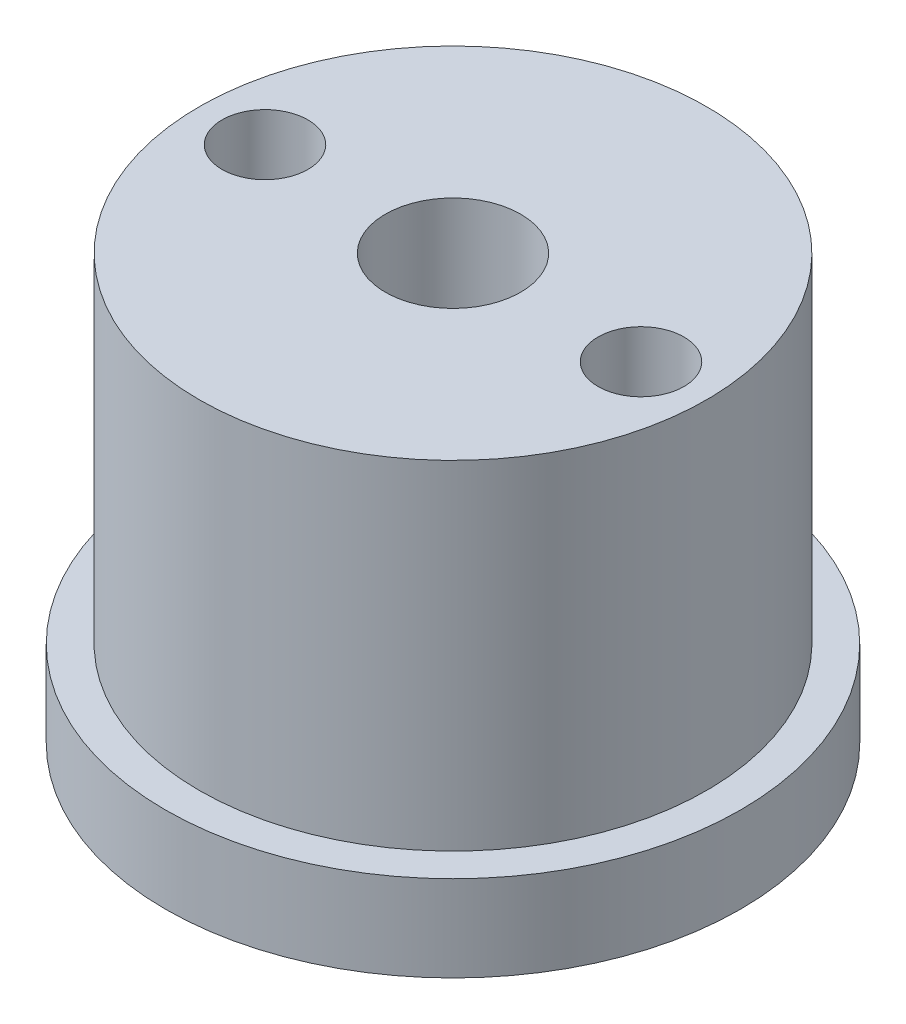
SolidWorks part; units mm, degrees
ref_plane "Front Plane" through (0, 0, 0) normal (0, 0, 1) x (1, 0, 0)
ref_plane "Top Plane" through (0, 0, 0) normal (0, 1, 0) x (1, 0, 0)
ref_plane "Right Plane" through (0, 0, 0) normal (1, 0, 0) x (0, 0, -1)
sketch "Sketch1" plane through (0, 0, 0) normal (0, 0, 1) x (1, 0, 0)
  line L0 (-7.5, 0) -> (-8.5, 0)
  line L1 (-7.5, 10) -> (0, 10)
  line L2 (-7.5, 10) -> (-7.5, 0)
  line L3 (-7.5, 0) -> (0, 0) construction
  line L4 (0, 10) -> (0, 0) construction
  line L5 (-8.5, 0) -> (-8.5, -2.54)
  line L6 (-8.5, -2.54) -> (0, -2.54)
  line L7 (0, -2.54) -> (0, 0) construction
  line L8 (0, 10) -> (0, -2.54)
  dimension "D1" = 15
  dimension "D2" = 10
  dimension "D3" = 1
  dimension "D4" = 2.54
revolve "Revolve1" add sketch "Sketch1" angle 360 about L8
sketch "Sketch2" plane through (0, 10, 0) normal (0, 1, 0) x (1, 0, 0)
  line L0 (5.5562, 0) -> (-5.5562, 0) construction
  circle A0 centre (-5.5562, 0) radius 1.27
  circle A1 centre (5.5562, 0) radius 1.27
  point P6 (0, 0)
  dimension "D2" = 2.54
  dimension "D1" = 11.1125
extrude "Cut-Extrude1" cut sketch "Sketch2" against normal blind 12.7
sketch "Sketch3" plane through (0, -2.54, 0) normal (0, -1, 0) x (1, 0, 0)
  circle A0 centre (0, 0) radius 2
  dimension "D1" = 4
extrude "Cut-Extrude2" cut sketch "Sketch3" against normal through all
